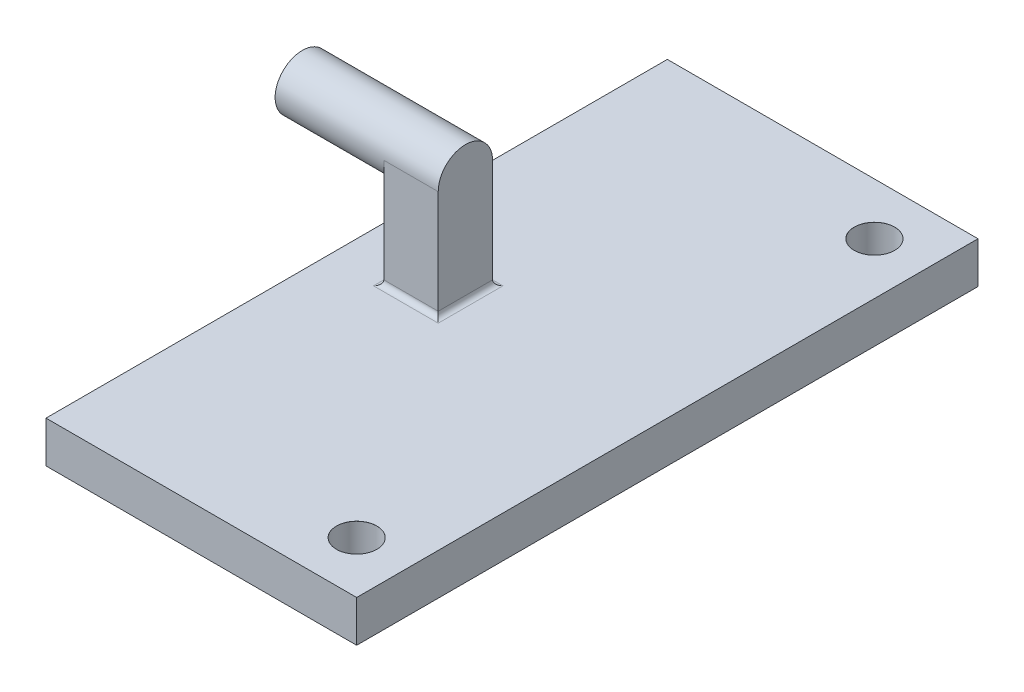
SolidWorks part; units mm, degrees
material "Plain Carbon Steel"
ref_plane "Front Plane" through (0, 0, 0) normal (0, 0, 1) x (1, 0, 0)
ref_plane "Top Plane" through (0, 0, 0) normal (0, 1, 0) x (1, 0, 0)
ref_plane "Right Plane" through (0, 0, 0) normal (1, 0, 0) x (0, 0, -1)
sketch "Sketch1" plane through (0, 0, 0) normal (1, 0, 0) x (0, 0, -1)
  circle A0 centre (0, 0) radius 26.25
extrude "Boss-Extrude1" add sketch "Sketch1" along normal blind 105
sketch "Sketch2" plane through (105, 0, 0) normal (1, 0, 0) x (0, 0, -1)
  line L1 (-26.25, 0) -> (-26.25, -105)
  line L2 (-26.25, -105) -> (26.25, -105)
  line L3 (26.25, -105) -> (26.25, 0)
  circle A0 centre (0, 0) radius 26.25 construction
  arc A1 (-26.25, 0) -> (26.25, 0) centre (0, 0) cw
extrude "Boss-Extrude2" add sketch "Sketch2" along normal blind 52.5
sketch "Sketch6" plane through (0, 0, 0) normal (-1, 0, 0) x (0, 0, 1)
  point P0 (0, 0)
hole_wizard "Tap Drill for M24x2.0 Tap1" positions "Sketch6" profile "Sketch4" hole size "M24x2.0" standard "ISO"
sketch "Sketch4" plane through (0, 0, 0) normal (0, 1, 0) x (0, 0, 1)
  line L0 (0, 0) -> (0, 111.6095)
  line L1 (0, 111.6095) -> (11, 105)
  line L2 (11, 105) -> (11, 0.025)
  line L3 (11, 0.025) -> (11.025, 0)
  line L5 (11.025, 0) -> (0, 0)
  line L6 (-11, 0.025) -> (-11.025, 0) construction
  line L10 (0, 111.6095) -> (-11, 105) construction
  line L11 (0, -6.35) -> (0, 107.95) construction
  dimension "Hole Dia." = 22
  dimension "Hole Depth" = 105
  dimension "Near C'Sink Dia." = 22.05
  dimension "Near C'Sink Angle" = 90
  dimension "Drill Angle" = 118
sketch "Sketch7" plane through (0, -105, 0) normal (0, -1, 0) x (1, 0, 0)
  line L0 (157.5, -26.25) -> (157.5, -13.7439)
  line L8 (52.5, 300) -> (352.5, 300)
  line L10 (352.5, -300) -> (52.5, -300)
  line L11 (352.5, 300) -> (352.5, -300)
  line L13 (52.5, 0) -> (52.5, 300)
  line L14 (52.5, 0) -> (52.5, -300)
  dimension "D1" = 300
extrude "Boss-Extrude3" add sketch "Sketch7" along normal blind 40 contours L8 L11 L10 L14 L13
fillet "Fillet1" radius 5 4 edges at (157.5, -105, 0) (131.25, -105, -26.25) (105, -105, 0) (131.25, -105, 26.25)
sketch "Sketch10" plane through (0, -105, 0) normal (0, 1, 0) x (1, 0, 0)
  line L0 (352.5, 300) -> (52.5, 300) construction
  line L1 (352.5, -300) -> (352.5, 300) construction
  line L2 (52.5, -300) -> (352.5, -300) construction
  point P0 (302.5, -250)
  point P2 (302.5, 250)
  dimension "D1" = 50
  dimension "D2" = 50
  dimension "D3" = 50
  dimension "D4" = 50
hole_wizard "Tap Drill for M42x3.0 Tap1" positions "Sketch10" profile "Sketch9" hole size "M42x3.0" standard "ISO" end condition through all
sketch "Sketch9" plane through (302.5, -105, 250) normal (1, 0, 0) x (0, 0, 1)
  line L0 (0, 0) -> (0, 40)
  line L1 (0, 40) -> (19.5, 40)
  line L2 (19.5, 40) -> (19.5, 0.025)
  line L3 (19.5, 0.025) -> (19.525, 0)
  line L5 (19.525, 0) -> (0, 0)
  line L6 (-19.5, 0.025) -> (-19.525, 0) construction
  line L11 (0, -6.35) -> (0, 107.95) construction
  dimension "Thru Hole Dia." = 39
  dimension "Thru Hole Depth" = 40
  dimension "Near C'Sink Dia." = 39.05
  dimension "Near C'Sink Angle" = 90
